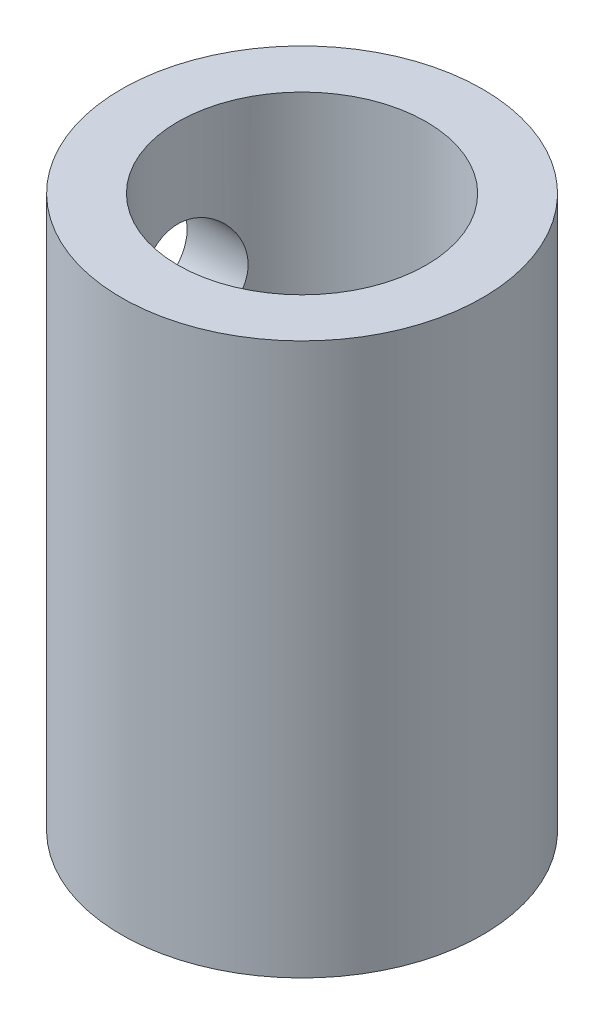
SolidWorks part; units mm, degrees
ref_plane "Front" through (0, 0, 0) normal (0, 0, 1) x (1, 0, 0)
ref_plane "Top" through (0, 0, 0) normal (0, 1, 0) x (1, 0, 0)
ref_plane "Right" through (0, 0, 0) normal (1, 0, 0) x (0, 0, -1)
sketch "Sketch1" plane through (0, 0, 0) normal (0, 0, 1) x (1, 0, 0)
  line L0 (2.955, 4) -> (2.955, 0)
  line L1 (2.955, 0) -> (4.8, 0)
  line L2 (4.8, 0) -> (4.8, 14.66)
  line L3 (4.8, 14.66) -> (3.3, 14.66)
  line L4 (3.3, 14.66) -> (3.3, 5.3)
  line L6 (0, 0) -> (0, 2.7677) construction
  line L8 (2.955, 4) -> (1.515, 4)
  line L11 (1.515, 4) -> (1.515, 5)
  line L12 (1.515, 5) -> (0, 5)
  line L14 (3.3, 5.3) -> (0, 5.3)
  line L15 (0, 5) -> (0, 5.3)
  point P15 (0, 0)
  point P16 (0, 0)
  dimension "D1" = 2.955
  dimension "D2" = 3.3
  dimension "D3" = 1.5
  dimension "D4" = 4
  dimension "D6" = 1.515
  dimension "D7" = 1
  dimension "D8" = 0.3
revolve "Revolve1" add sketch "Sketch1" angle 360 about L6
sketch "Sketch2" plane through (0, 0, 0) normal (1, 0, 0) x (0, 0, -1)
  circle A0 centre (0, 10.8037) radius 1.505
  dimension "D1" = 3.01
extrude "Cut-Extrude1" cut sketch "Sketch2" against normal up to surface (4.558 mm away)
